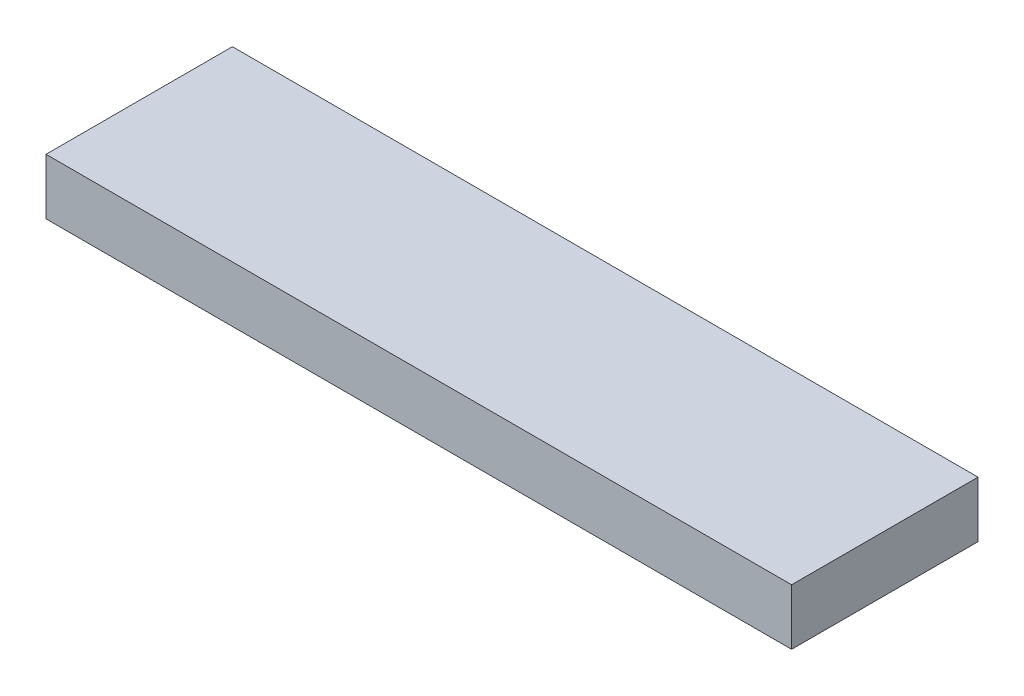
SolidWorks part; units mm, degrees
ref_plane "Front Plane" through (0, 0, 0) normal (0, 0, 1) x (1, 0, 0)
ref_plane "Top Plane" through (0, 0, 0) normal (0, 1, 0) x (1, 0, 0)
ref_plane "Right Plane" through (0, 0, 0) normal (1, 0, 0) x (0, 0, -1)
sketch "Sketch1" plane through (0, 0, 0) normal (0, 1, 0) x (1, 0, 0)
  line L1 (-100, -25) -> (100, -25)
  line L2 (-100, -25) -> (-100, 25)
  line L3 (-100, 25) -> (100, 25)
  line L4 (100, -25) -> (100, 25)
  line L5 (-100, -25) -> (100, 25) construction
  line L6 (-100, 25) -> (100, -25) construction
  point P0 (0, 0)
  dimension "D1" = 200
  dimension "D2" = 50
extrude "Boss-Extrude1" add sketch "Sketch1" along normal mid plane 15
